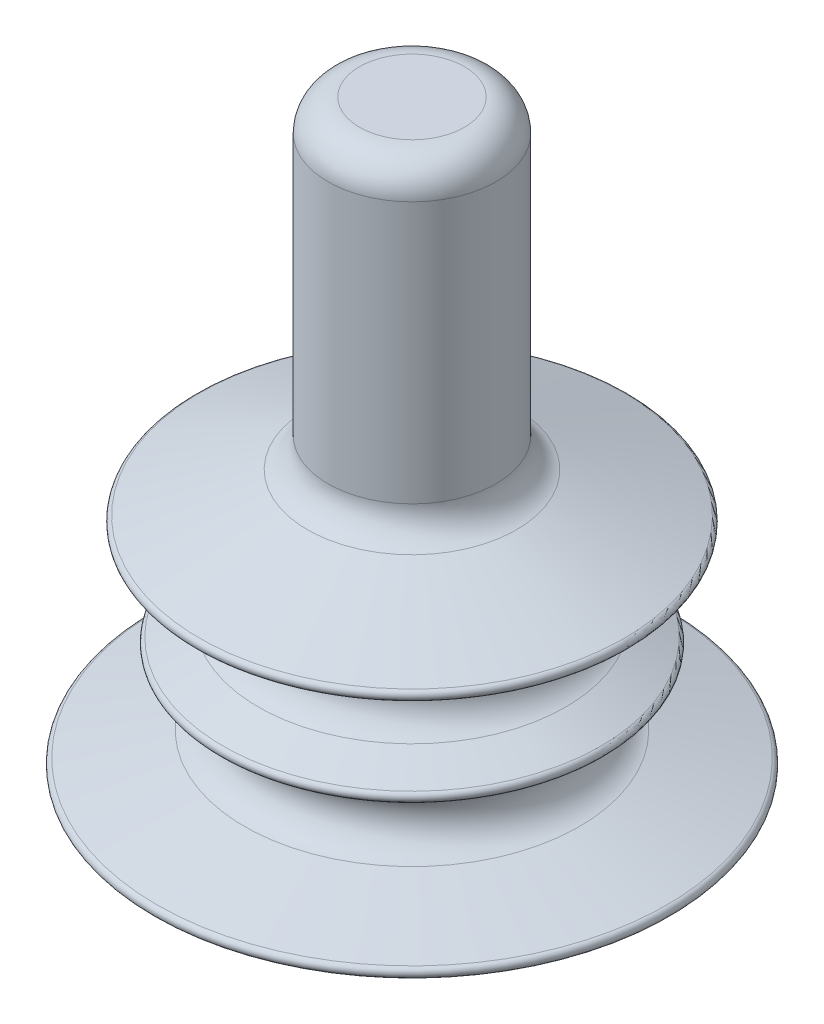
SolidWorks part; units mm, degrees
ref_plane "Plano frontal" through (0, 0, 0) normal (0, 0, 1) x (1, 0, 0)
ref_plane "Plano superior" through (0, 0, 0) normal (0, 1, 0) x (1, 0, 0)
ref_plane "Plano direito" through (0, 0, 0) normal (1, 0, 0) x (0, 0, -1)
sketch "Esboço1" plane through (0, 0, 0) normal (1, 0, 0) x (0, 0, -1)
  line L0 (0, 0) -> (0, 65) construction
  line L1 (0, 65) -> (-8, 65)
  line L2 (-8, 65) -> (-8, 35)
  line L3 (-8, 35) -> (-20.234, 30.4689)
  line L4 (-20.234, 29.5311) -> (-8, 25)
  line L5 (-21.5, 30) -> (0, 30) construction
  line L6 (-8, 25) -> (-17.9986, 20.4552)
  line L7 (-17.9986, 19.5448) -> (-8, 15)
  line L8 (-8, 15) -> (-24.2657, 10.4818)
  line L9 (-24.2657, 9.5182) -> (-8, 5)
  line L10 (-8, 5) -> (-8, 0)
  line L11 (-8, 0) -> (0, 0)
  line L12 (-19, 20) -> (0, 20) construction
  line L13 (-26, 10) -> (0, 10) construction
  line L14 (0, 0) -> (0, 65)
  arc A0 (-20.234, 30.4689) -> (-20.234, 29.5311) centre (-20.0604, 30) ccw
  arc A1 (-17.9986, 20.4552) -> (-17.9986, 19.5448) centre (-17.7917, 20) ccw
  arc A2 (-24.2657, 10.4818) -> (-24.2657, 9.5182) centre (-24.1318, 10) ccw
  dimension "D13" = 0.5
  dimension "D1" = 5
  dimension "D4" = 30
  dimension "D3" = 8
  dimension "D7" = 21.5
  dimension "D6" = 10
  dimension "D8" = 19
  dimension "D9" = 10
  dimension "D5" = 5
  dimension "D10" = 5
  dimension "D11" = 26
  dimension "D2" = 10
  dimension "D12" = 5
revolve "Revolução1" add sketch "Esboço1" angle 360 about L14
fillet "Filete1" radius 3 5 edges at (0, 65, -8) (0, 5, -8) (0, 15, -8) (0, 25, -8) (0, 35, -8)
equation "\"D5@Esboço1\"=\"D6@Esboço1\"/2"
equation "\"D10@Esboço1\"=\"D9@Esboço1\"/2"
